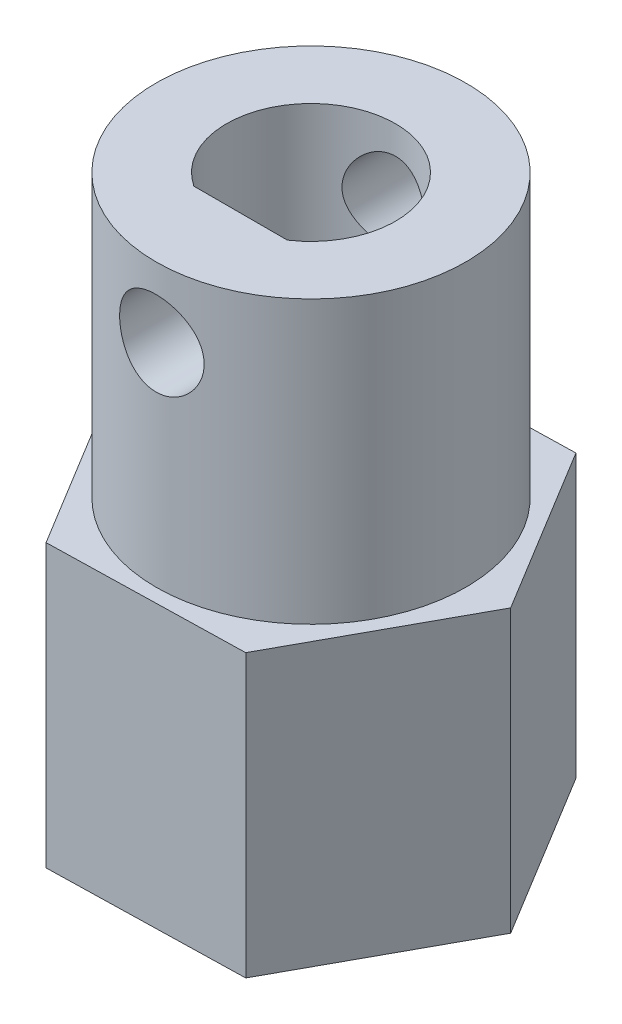
SolidWorks part; units mm, degrees
ref_plane "前视基准面" through (0, 0, 0) normal (0, 0, 1) x (1, 0, 0)
ref_plane "上视基准面" through (0, 0, 0) normal (0, 1, 0) x (1, 0, 0)
ref_plane "右视基准面" through (0, 0, 0) normal (1, 0, 0) x (0, 0, -1)
sketch "草图1" plane through (0, 0, 0) normal (0, 1, 0) x (1, 0, 0)
  line L1 (3.6023, -5.9181) -> (6.9263, 0.1607)
  line L2 (6.9263, 0.1607) -> (3.324, 6.0787)
  line L3 (3.324, 6.0787) -> (-3.6023, 5.9181)
  line L4 (-3.6023, 5.9181) -> (-6.9263, -0.1607)
  line L5 (-6.9263, -0.1607) -> (-3.324, -6.0787)
  line L6 (-3.324, -6.0787) -> (3.6023, -5.9181)
  circle A0 centre (0, 0) radius 6 construction
  dimension "D1" = 12
extrude "凸台-拉伸1" add sketch "草图1" along normal blind 10
sketch "草图2" plane through (0, 10, 0) normal (0, 1, 0) x (1, 0, 0)
  circle A0 centre (0, 0) radius 5.5
  dimension "D1" = 11
extrude "凸台-拉伸2" add sketch "草图2" along normal blind 10
sketch "草图3" plane through (0, 20, 0) normal (0, 1, 0) x (1, 0, 0)
  line L0 (0, 3) -> (0, -3)
  line L1 (0, 3) -> (0, -2.5)
  line L2 (-1.6583, -2.5) -> (1.6583, -2.5)
  circle A0 centre (0, 0) radius 3
  point P3 (-1.6583, -2.5)
  point P6 (0, 0)
  point P7 (1.6583, -2.5)
  point P11 (0, -2.5)
  dimension "D1" = 6
  dimension "D2" = 5.5
extrude "切除-拉伸1" cut sketch "草图3" against normal blind 11.5 contours L0 A0 L2 | L2 A0 L0
sketch "草图4" plane through (0, 0, 2.5) normal (0, 0, -1) x (-1, 0, 0)
  line L0 (1.6583, 20) -> (-1.6583, 20) construction
  circle A0 centre (0, 17.5) radius 1.5
  dimension "D1" = 3
  dimension "D2" = 2.5
extrude "切除-拉伸3" cut sketch "草图4" against normal through all and the other way through all contours A0
sketch "草图6" plane through (0, 8.5, 0) normal (0, 1, 0) x (1, 0, 0)
  circle A0 centre (0, 0) radius 1.5
  dimension "D1" = 3
extrude "切除-拉伸4" cut sketch "草图6" against normal through all contours A0
